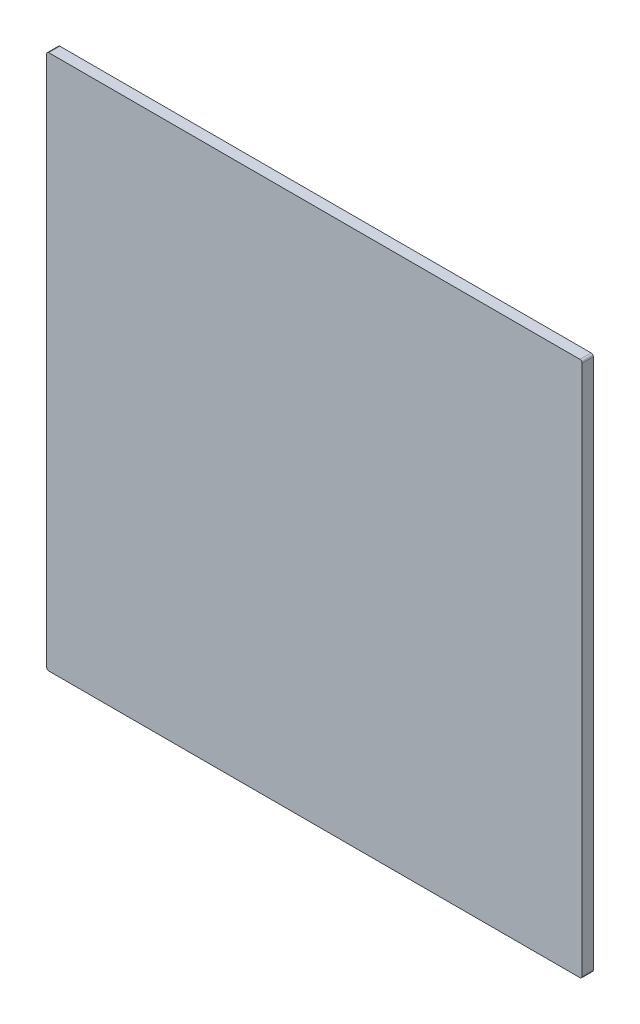
SolidWorks part; units mm, degrees
ref_plane "Front Plane" through (0, 0, 0) normal (0, 0, 1) x (1, 0, 0)
ref_plane "Top Plane" through (0, 0, 0) normal (0, 1, 0) x (1, 0, 0)
ref_plane "Right Plane" through (0, 0, 0) normal (1, 0, 0) x (0, 0, -1)
sketch "Sketch1" plane through (0, 0, 0) normal (0, 0, 1) x (1, 0, 0)
  line L1 (-224.9767, 260.7264) -> (384.6233, 260.7264)
  line L2 (-224.9767, 260.7264) -> (-224.9767, -348.8736)
  line L3 (-224.9767, -348.8736) -> (384.6233, -348.8736)
  line L4 (384.6233, 260.7264) -> (384.6233, -348.8736)
  dimension "D1" = 609.6
  dimension "D2" = 609.6
extrude "Boss-Extrude1" add sketch "Sketch1" along normal blind 12.7 contours L2 L3 L4 L1
fillet "Fillet1" radius 2.54 4 edges at (-224.9767, -348.8736, 6.35) (384.6233, -348.8736, 6.35) (384.6233, 260.7264, 6.35) (-224.9767, 260.7264, 6.35)
